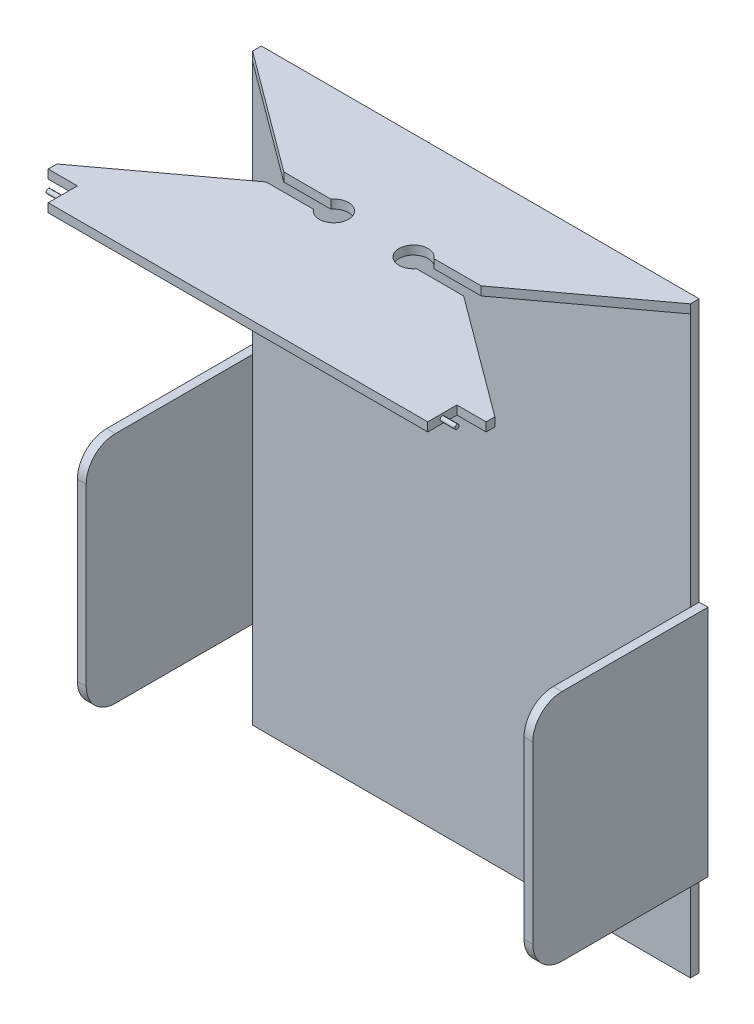
SolidWorks part; units mm, degrees
ref_plane "Plan de face" through (0, 0, 0) normal (0, 0, 1) x (1, 0, 0)
ref_plane "Plan de dessus" through (0, 0, 0) normal (0, 1, 0) x (1, 0, 0)
ref_plane "Plan de droite" through (0, 0, 0) normal (1, 0, 0) x (0, 0, -1)
sketch "Esquisse1" plane through (0, 0, 0) normal (0, 0, 1) x (1, 0, 0)
  line L1 (0, 0) -> (150, 0)
  line L2 (0, 0) -> (0, -200)
  line L3 (0, -200) -> (150, -200)
  line L4 (150, 0) -> (150, -200)
  dimension "D1" = 150
  dimension "D2" = 200
extrude "Boss.-Extru.1" add sketch "Esquisse1" along normal blind 3
sketch "Esquisse2" plane through (0, 0, 3) normal (0, 0, 1) x (1, 0, 0)
  line L0 (150, -200) -> (150, 0) construction
  line L1 (0, 0) -> (150, 0)
  line L2 (0, 0) -> (0, -3)
  line L3 (0, -3) -> (150, -3)
  line L4 (150, 0) -> (150, -3)
  dimension "D1" = 3
extrude "Boss.-Extru.2" add sketch "Esquisse2" along normal blind 80
sketch "Esquisse3" plane through (0, 0, 0) normal (0, 1, 0) x (1, 0, 0)
  line L0 (75, 0) -> (75, -83) construction
  line L1 (0, -83) -> (10, -83)
  line L2 (0, -83) -> (0, -73)
  line L3 (0, -73) -> (10, -73)
  line L4 (10, -83) -> (10, -73)
  line L5 (150, 0) -> (0, 0) construction
  line L6 (150, -83) -> (0, -83) construction
  line L7 (150, -83) -> (140, -83)
  line L8 (150, -83) -> (150, -73)
  line L9 (140, -83) -> (140, -73)
  line L10 (150, -73) -> (140, -73)
  dimension "D1" = 10
  dimension "D2" = 10
extrude "Enlèv. mat.-Extru.1" cut sketch "Esquisse3" against normal blind 80
sketch "Esquisse4" plane through (140, 0, 0) normal (1, 0, 0) x (0, 0, -1)
  line L0 (-78, 0) -> (-78, -3) construction
  line L1 (-73, 0) -> (-83, 0) construction
  line L2 (-73, -3) -> (-83, -3) construction
  line L3 (-83, -1.5) -> (-73, -1.5) construction
  line L4 (-83, 0) -> (-83, -3) construction
  line L5 (-73, -3) -> (-73, 0) construction
  circle A0 centre (-78, -1.5) radius 0.75
extrude "Boss.-Extru.3" add sketch "Esquisse4" along normal blind 5
sketch "Esquisse6" plane through (10, 0, 0) normal (-1, 0, 0) x (0, 0, 1)
  line L0 (78, 0) -> (78, -3) construction
  line L1 (83, 0) -> (73, 0) construction
  line L2 (83, -3) -> (73, -3) construction
  line L3 (73, -1.5) -> (83, -1.5) construction
  line L4 (73, -3) -> (73, 0) construction
  line L5 (83, -3) -> (83, 0) construction
  circle A0 centre (78, -1.5) radius 0.75
extrude "Boss.-Extru.5" add sketch "Esquisse6" along normal blind 5
sketch "Esquisse9" plane through (0, 0, 0) normal (0, 1, 0) x (1, 0, 0)
  line L0 (75, -83) -> (75, 0) construction
  line L1 (140, -83) -> (10, -83) construction
  line L2 (150, 0) -> (0, 0) construction
  line L3 (0, -36.5) -> (150, -36.5) construction
  line L4 (0, -73) -> (0, 0) construction
  line L5 (150, -73) -> (150, 0) construction
  line L6 (0, -3) -> (41.1893, -33.5)
  line L7 (0, -70) -> (41.1893, -39.5)
  line L8 (41.1893, -33.5) -> (57.3611, -33.5)
  line L9 (41.1893, -39.5) -> (57.3611, -39.5)
  line L10 (150, -70) -> (108.8107, -39.5)
  line L11 (108.8107, -39.5) -> (92.6389, -39.5)
  line L12 (108.8107, -33.5) -> (92.6389, -33.5)
  line L13 (150, -3) -> (108.8107, -33.5)
  circle A0 centre (61.3611, -36.5) radius 5
  circle A1 centre (88.6389, -36.5) radius 5
  point P12 (0, -3)
  line M6 (150, -73) -> (150, 0)
  line M8 (0, 0) -> (0, -73)
  dimension "D3" = 10
  dimension "D1" = 3
  dimension "D2" = 3
extrude "Enlèv. mat.-Extru.2" cut sketch "Esquisse9" against normal blind 3 contours A0 L8 L6 L7 L9 M8 | A0 | L12 A1 L11 L10 L13 M6 | A1 M8
sketch "Esquisse10" plane through (0, 0, 0) normal (-1, 0, 0) x (0, 0, 1)
  line L0 (3, -3) -> (3, -200) construction
  line L1 (3, 0) -> (33.5, 0) construction
  line L2 (0, -170) -> (0, -90)
  line L3 (0, 0) -> (0, -200) construction
  line L4 (0, -90) -> (60, -90)
  line L5 (60, -90) -> (60, -170)
  line L6 (60, -170) -> (0, -170)
  point P0 (3, -90)
  point P5 (3, -170)
  dimension "D1" = 90
  dimension "D2" = 170
  dimension "D3" = 60
extrude "Boss.-Extru.9" add sketch "Esquisse10" along normal blind 3
sketch "Esquisse11" plane through (150, 0, 0) normal (1, 0, 0) x (0, 0, -1)
  line L0 (0, -90) -> (-60, -90)
  line L1 (-60, -90) -> (-60, -170)
  line L2 (-60, -170) -> (0, -170)
  line L3 (0, -170) -> (0, -90)
extrude "Boss.-Extru.10" add sketch "Esquisse11" along normal blind 3
fillet "Congé1" radius 10 4 edges at (151.5, -170, 60) (-1.5, -170, 60) (151.5, -90, 60) (-1.5, -90, 60)
